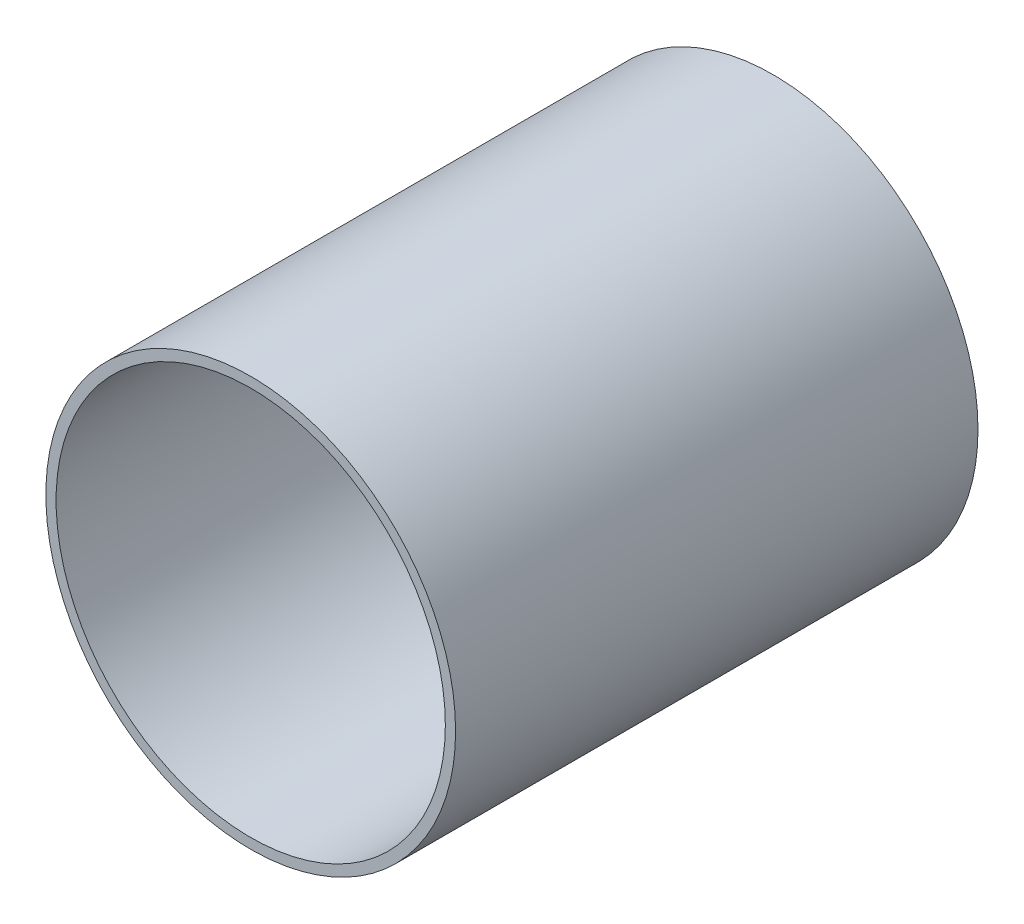
SolidWorks part; units mm, degrees
material "6061 合金"
ref_plane "前视基准面" through (0, 0, 0) normal (0, 0, 1) x (1, 0, 0)
ref_plane "上视基准面" through (0, 0, 0) normal (0, 1, 0) x (1, 0, 0)
ref_plane "右视基准面" through (0, 0, 0) normal (1, 0, 0) x (0, 0, -1)
sketch "草图1" plane through (0, 0, 0) normal (0, 0, 1) x (1, 0, 0)
  circle A0 centre (0, 0) radius 9.5
  circle A1 centre (0, 0) radius 10
  dimension "D1" = 9.5
  dimension "D2" = 10
extrude "凸台-拉伸1" add sketch "草图1" along normal blind 25.5
